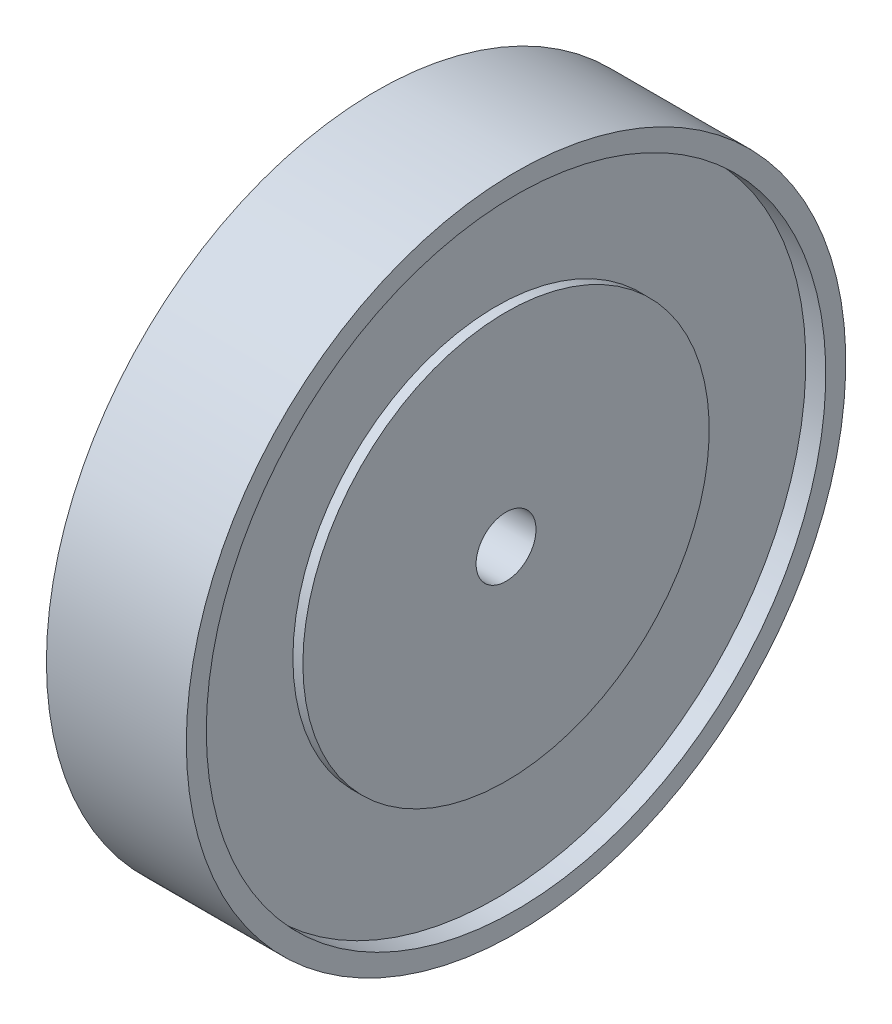
SolidWorks part; units mm, degrees
ref_plane "Front Plane" through (0, 0, 0) normal (0, 0, 1) x (1, 0, 0)
ref_plane "Top Plane" through (0, 0, 0) normal (0, 1, 0) x (1, 0, 0)
ref_plane "Right Plane" through (0, 0, 0) normal (1, 0, 0) x (0, 0, -1)
sketch "Sketch3" plane through (0, 0, 0) normal (0, 0, 1) x (1, 0, 0)
  line L0 (0, 0) -> (0, 93.3201) construction
  line L1 (0, 0) -> (122.7839, 0) construction
  line L2 (0, 15) -> (0, 165)
  line L3 (-35, 165) -> (35, 165)
  line L4 (35, 165) -> (35, 155)
  line L5 (35, 155) -> (25, 155)
  line L7 (25, 15) -> (-25, 15)
  line L8 (-35, 155) -> (-25, 155)
  line L10 (-35, 165) -> (-35, 155)
  line L11 (25, 155) -> (25, 101.6658)
  line L12 (25, 101.6658) -> (30, 101.6658)
  line L13 (30, 101.6658) -> (30, 15)
  line L14 (30, 15) -> (25, 15)
  line L15 (-30, 101.6658) -> (-30, 15)
  line L16 (-25, 101.6658) -> (-30, 101.6658)
  line L17 (-25, 155) -> (-25, 101.6658)
  line L18 (-25, 15) -> (-30, 15)
  dimension "D1" = 35
  dimension "D2" = 15
  dimension "D3" = 5
  dimension "D4" = 10
  dimension "D5" = 10
  dimension "D6" = 150
revolve "Revolve1" add sketch "Sketch3" angle 360 about L1
